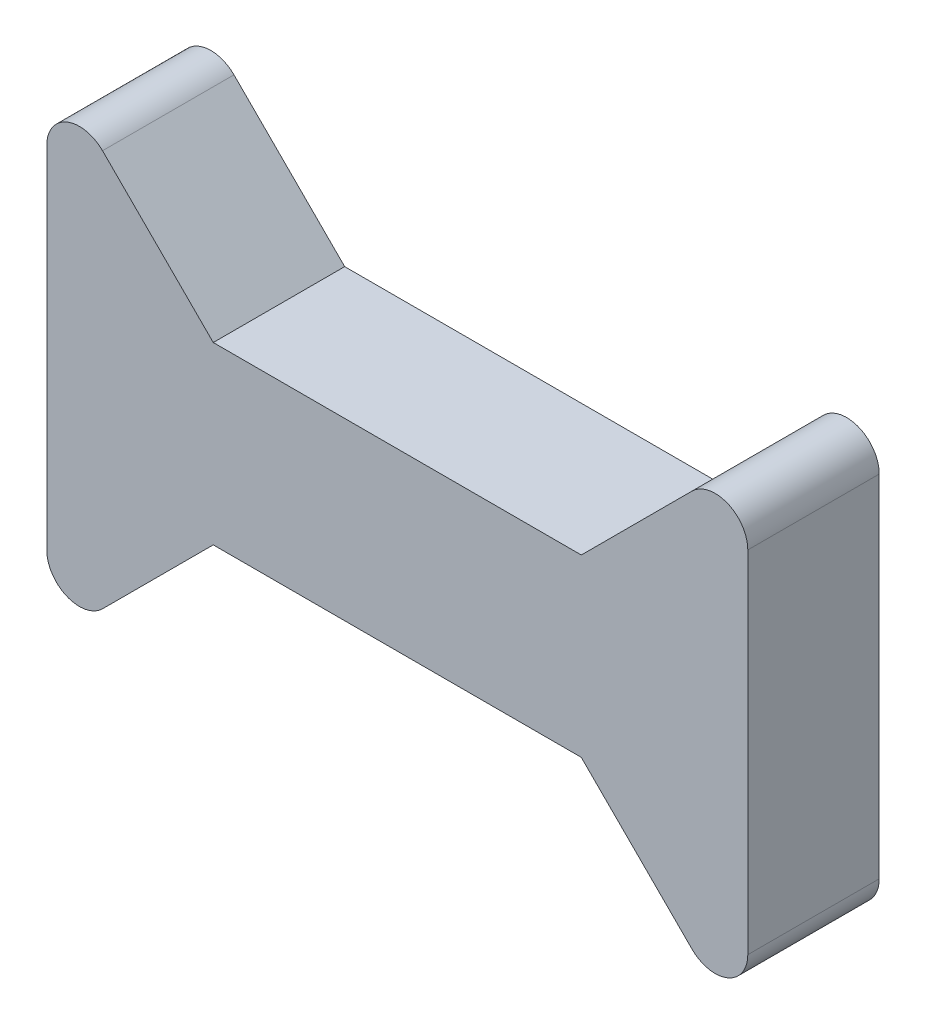
SolidWorks part; units mm, degrees
ref_plane "Front Plane" through (0, 0, 0) normal (0, 0, 1) x (1, 0, 0)
ref_plane "Top Plane" through (0, 0, 0) normal (0, 1, 0) x (1, 0, 0)
ref_plane "Right Plane" through (0, 0, 0) normal (1, 0, 0) x (0, 0, -1)
sketch "Sketch1" plane through (0, 0, 0) normal (0, 0, 1) x (1, 0, 0)
  line L0 (0, -5) -> (0, 5) construction
  line L1 (-20, 0) -> (20, 0) construction
  line L2 (-10.5, 5) -> (10.5, 5)
  line L3 (10.5, 5) -> (16.818, 11.318)
  line L4 (20, 10) -> (20, -10)
  line L5 (10.5, -5) -> (16.818, -11.318)
  line L6 (-10.5, -5) -> (10.5, -5)
  line L7 (-10.5, -5) -> (-16.818, -11.318)
  line L8 (-20, 10) -> (-20, -10)
  line L9 (-10.5, 5) -> (-16.818, 11.318)
  arc A0 (16.818, 11.318) -> (20, 10) centre (18.136, 10) cw
  arc A1 (16.818, -11.318) -> (20, -10) centre (18.136, -10) ccw
  arc A2 (-16.818, -11.318) -> (-20, -10) centre (-18.136, -10) cw
  arc A3 (-16.818, 11.318) -> (-20, 10) centre (-18.136, 10) ccw
  point P4 (0, 0)
  point P8 (0, 0)
  dimension "D1" = 135
  dimension "D2" = 10
  dimension "D3" = 20
  dimension "D4" = 20
  dimension "D5" = 10.5
extrude "Boss-Extrude1" add sketch "Sketch1" along normal blind 7.5
